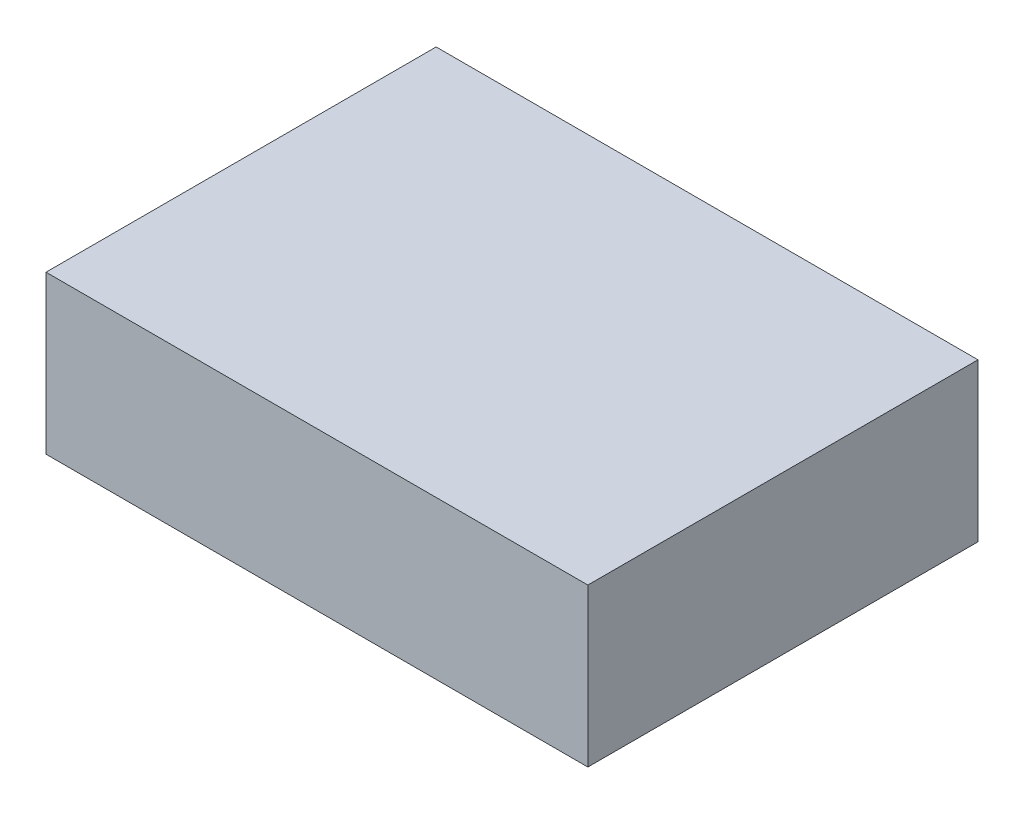
SolidWorks part; units mm, degrees
ref_plane "Front Plane" through (0, 0, 0) normal (0, 0, 1) x (1, 0, 0)
ref_plane "Top Plane" through (0, 0, 0) normal (0, 1, 0) x (1, 0, 0)
ref_plane "Right Plane" through (0, 0, 0) normal (1, 0, 0) x (0, 0, -1)
sketch "Sketch1" plane through (0, 0, 0) normal (0, 1, 0) x (1, 0, 0)
  line L1 (-34.925, -25.146) -> (34.925, -25.146)
  line L2 (-34.925, -25.146) -> (-34.925, 25.146)
  line L3 (-34.925, 25.146) -> (34.925, 25.146)
  line L4 (34.925, -25.146) -> (34.925, 25.146)
  line L5 (-34.925, -25.146) -> (34.925, 25.146) construction
  line L6 (-34.925, 25.146) -> (34.925, -25.146) construction
  point P0 (0, 0)
  dimension "D1" = 50.292
  dimension "D2" = 69.85
extrude "Boss-Extrude1" add sketch "Sketch1" along normal blind 20.32
